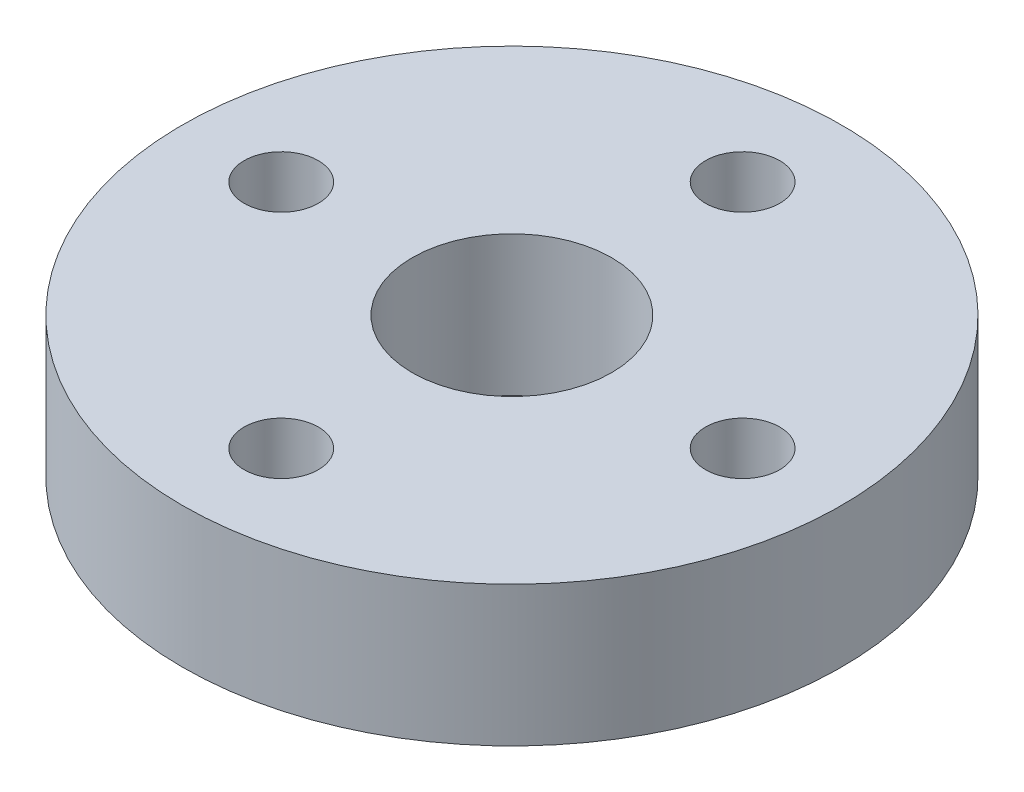
SolidWorks part; units mm, degrees
ref_plane "Front Plane" through (0, 0, 0) normal (0, 0, 1) x (1, 0, 0)
ref_plane "Top Plane" through (0, 0, 0) normal (0, 1, 0) x (1, 0, 0)
ref_plane "Right Plane" through (0, 0, 0) normal (1, 0, 0) x (0, 0, -1)
sketch "Sketch1" plane through (0, 0, 0) normal (0, 1, 0) x (1, 0, 0)
  circle A0 centre (0, 0) radius 10
  circle A1 centre (0, 0) radius 3.025
  dimension "D1" = 20
  dimension "D2" = 6.05
extrude "Boss-Extrude1" add sketch "Sketch1" along normal blind 4.25
sketch "Sketch3" plane through (0, 0, 0) normal (0, -1, 0) x (1, 0, 0)
  line L0 (0, 0) -> (0, 7) construction
  line L1 (7, 2.3094) -> (5, 1.1547)
  line L2 (-2.3094, 7) -> (-1.1547, 5)
  line L3 (-1.1547, 5) -> (1.1547, 5)
  line L4 (1.1547, 5) -> (2.3094, 7)
  line L5 (2.3094, 7) -> (1.1547, 9)
  line L6 (1.1547, 9) -> (-1.1547, 9)
  line L7 (-1.1547, 9) -> (-2.3094, 7)
  line L8 (5, 1.1547) -> (5, -1.1547)
  line L9 (5, -1.1547) -> (7, -2.3094)
  line L10 (7, -2.3094) -> (9, -1.1547)
  line L11 (9, -1.1547) -> (9, 1.1547)
  line L12 (9, 1.1547) -> (7, 2.3094)
  line L13 (0, 0) -> (7, 0) construction
  line L14 (2.3094, -7) -> (1.1547, -5)
  line L15 (1.1547, -5) -> (-1.1547, -5)
  line L16 (-1.1547, -5) -> (-2.3094, -7)
  line L17 (-2.3094, -7) -> (-1.1547, -9)
  line L18 (-1.1547, -9) -> (1.1547, -9)
  line L19 (1.1547, -9) -> (2.3094, -7)
  line L20 (0, 0) -> (0, -7) construction
  line L21 (-7, -2.3094) -> (-5, -1.1547)
  line L22 (-5, -1.1547) -> (-5, 1.1547)
  line L23 (-5, 1.1547) -> (-7, 2.3094)
  line L24 (-7, 2.3094) -> (-9, 1.1547)
  line L25 (-9, 1.1547) -> (-9, -1.1547)
  line L26 (-9, -1.1547) -> (-7, -2.3094)
  line L27 (0, 0) -> (-7, 0) construction
  circle A0 centre (0, 7) radius 2 construction
  circle A1 centre (7, 0) radius 2 construction
  circle A2 centre (0, -7) radius 2 construction
  circle A3 centre (-7, 0) radius 2 construction
  point P28 (0, 0)
  dimension "D1" = 4
  dimension "D2" = 14
  dimension "D3" = 4
extrude "Cut-Extrude1" cut sketch "Sketch3" against normal blind 2
sketch "Sketch4" plane through (0, 2, 0) normal (0, -1, 0) x (1, 0, 0)
  circle A0 centre (0, -7) radius 1.125
  circle A1 centre (0, 7) radius 1.125
  circle A2 centre (7, 0) radius 1.125
  circle A3 centre (-7, 0) radius 1.125
  dimension "D1" = 2.25
extrude "Cut-Extrude2" cut sketch "Sketch4" against normal through all
sketch "Sketch5" plane through (0, 0, 0) normal (0, -1, 0) x (1, 0, 0)
  circle A0 centre (0, 0) radius 10 construction
  circle A1 centre (7, 0) radius 1.125 construction
  circle A2 centre (0, -7) radius 1.125 construction
  circle A3 centre (-7, 0) radius 1.125 construction
  circle A4 centre (0, 7) radius 1.125 construction
  circle A5 centre (0, 0) radius 10
  circle A6 centre (7, 0) radius 1.125
  circle A7 centre (0, -7) radius 1.125
  circle A8 centre (-7, 0) radius 1.125
  circle A9 centre (0, 7) radius 1.125
  circle A10 centre (0, 0) radius 3.025 construction
  circle A11 centre (0, 0) radius 3.025
extrude "Boss-Extrude2" add sketch "Sketch5" against normal up to surface (4.25 mm away) up to face at (0, 4.25, -8.125)
shell "Shell1" thickness 1
